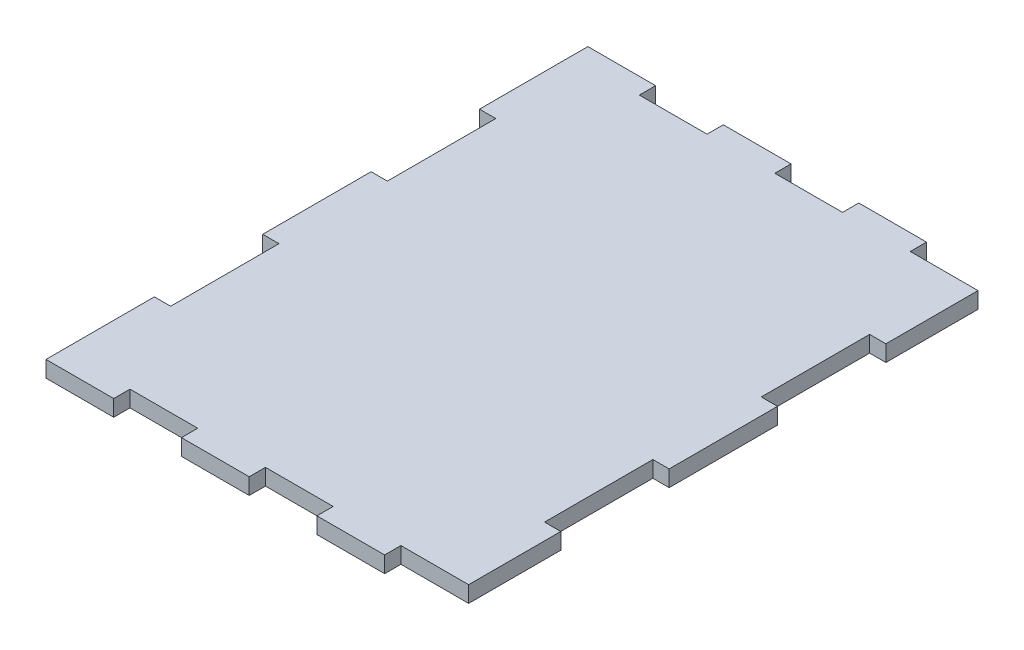
SolidWorks part; units mm, degrees
ref_plane "Front Plane" through (0, 0, 0) normal (0, 0, 1) x (1, 0, 0)
ref_plane "Top Plane" through (0, 0, 0) normal (0, 1, 0) x (1, 0, 0)
ref_plane "Right Plane" through (0, 0, 0) normal (1, 0, 0) x (0, 0, -1)
sketch "Sketch1" plane through (0, 0, 0) normal (0, 1, 0) x (1, 0, 0)
  line L1 (150, 0) -> (0, 0)
  line L2 (150, 0) -> (150, 200)
  line L3 (150, 200) -> (0, 200)
  line L4 (0, 0) -> (0, 200)
  dimension "D1" = 150
  dimension "D2" = 200
extrude "Boss-Extrude1" add sketch "Sketch1" along normal blind 6
sketch "Sketch2" plane through (0, 6, 0) normal (0, 1, 0) x (1, 0, 0)
  line L0 (0, 0) -> (150, 0) construction
  line L1 (25, 0) -> (50, 0)
  line L2 (25, 0) -> (25, 6)
  line L3 (25, 6) -> (50, 6)
  line L4 (50, 0) -> (50, 6)
  line L5 (0, 200) -> (0, 0) construction
  line L6 (75, 0) -> (75, 6)
  line L7 (75, 0) -> (100, 0)
  line L8 (100, 0) -> (100, 6)
  line L9 (75, 6) -> (100, 6)
  line L10 (125, 0) -> (125, 6)
  line L11 (125, 0) -> (150, 0)
  line L12 (150, 0) -> (150, 6)
  line L13 (125, 6) -> (150, 6)
  line L14 (25, 194) -> (25, 200)
  line L15 (25, 194) -> (50, 194)
  line L16 (50, 194) -> (50, 200)
  line L17 (25, 200) -> (50, 200)
  line L18 (75, 194) -> (75, 200)
  line L19 (75, 194) -> (100, 194)
  line L20 (100, 194) -> (100, 200)
  line L21 (75, 200) -> (100, 200)
  line L22 (125, 194) -> (125, 200)
  line L23 (125, 194) -> (150, 194)
  line L24 (150, 194) -> (150, 200)
  line L25 (125, 200) -> (150, 200)
  line L26 (150, 200) -> (0, 200) construction
  line L27 (0, 160) -> (6, 160)
  line L28 (0, 160) -> (0, 120)
  line L29 (0, 120) -> (6, 120)
  line L30 (6, 160) -> (6, 120)
  line L31 (144, 160) -> (144, 120)
  line L32 (144, 160) -> (150, 160)
  line L33 (150, 160) -> (150, 120)
  line L34 (144, 120) -> (150, 120)
  line L35 (144, 80) -> (144, 40)
  line L36 (144, 80) -> (150, 80)
  line L37 (150, 80) -> (150, 40)
  line L38 (144, 40) -> (150, 40)
  line L39 (0, 80) -> (0, 40)
  line L40 (0, 80) -> (6, 80)
  line L41 (6, 80) -> (6, 40)
  line L42 (0, 40) -> (6, 40)
  dimension "D1" = 25
  dimension "D2" = 25
  dimension "D3" = 6
  dimension "D6" = 40
  dimension "D7" = 40
  dimension "D8" = 6
  dimension "D4" = 3
  dimension "D5" = 2
  dimension "D9" = 2
  dimension "D10" = 2
extrude "Cut-Extrude1" cut sketch "Sketch2" against normal blind 6
